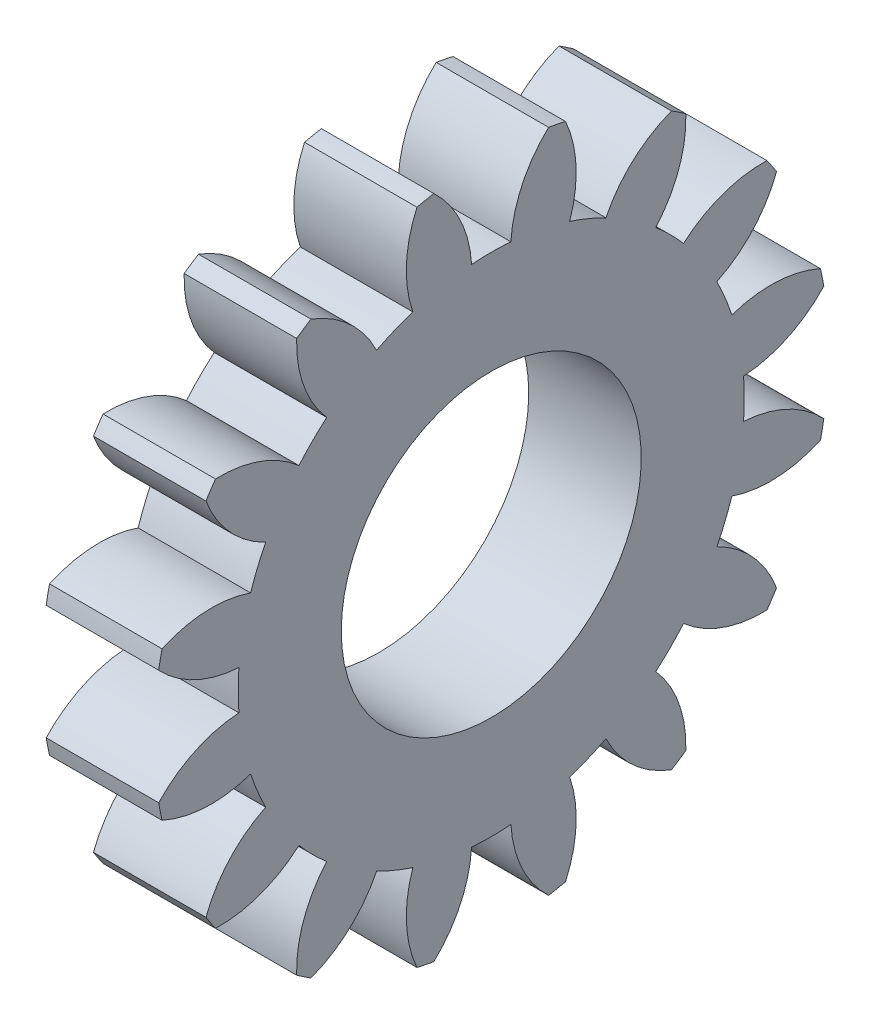
SolidWorks part; units mm, degrees
ref_plane "Plane1" through (0, 0, 0) normal (0, 0, 1) x (1, 0, 0)
ref_plane "Plane2" through (0, 0, 0) normal (0, 1, 0) x (1, 0, 0)
ref_plane "Plane3" through (0, 0, 0) normal (1, 0, 0) x (0, 0, -1)
sketch "HoldingSke" plane through (0, 0, 0) normal (0, 1, 0) x (1, 0, 0)
  line L0 (0, 0) -> (0.9613, -0.2756)
  line L1 (-15, 0) -> (100, 0) construction
  line L2 (0, 0) -> (-2.1039, 2.3779)
  line L3 (0, 0) -> (-11.863, 4.5341)
  line L4 (0, 0) -> (8.3015, 2.3804)
  line L5 (0, 0) -> (-46.8476, -17.4728)
  line L6 (0, 0) -> (-2.4869, -1.6779)
  line L7 (-2.1039, 2.3779) -> (8.6586, 51.2059)
  line L8 (-76.2, 54.61) -> (-74.8, 54.61)
  line L9 (-71.009, 38.7566) -> (-53.1078, 45.2721)
  line L10 (-76.2, 71.12) -> (104.1128, 71.12)
  line L11 (0, 0) -> (-3, 0)
  line L12 (-76.2, 101.6) -> (-76.162, 101.6)
  line L13 (24.9733, 27.94) -> (52.9518, 28.4284)
  line L14 (24.9733, 27.94) -> (24.9743, 27.94)
  line L15 (24.9733, 27.94) -> (100.4006, 29.5858)
  line L16 (-63.627, -1) -> (-12.827, -1)
  circle A0 centre (0, 0) radius 4
  circle A1 centre (0, 0) radius 6.749
  circle A2 centre (0, 0) radius 37.5
  circle A3 centre (0, 0) radius 4
  dimension "MHD" = 13.498
  dimension "Hub_dia" = 75
  dimension "Bore" = 8
  dimension "MBD" = 8
  dimension "Num_teeth" = 16
  dimension "Pitch_radius" = 180.3128
  dimension "Pitch" = 1
  dimension "Width" = 3
  dimension "Overall_len" = 50
  dimension "Show_teeth" = 16
  dimension "Thickness" = 3
  dimension "OAL" = 50.0001
  dimension "T_dim" = 1.4
  dimension "Ap" = 20
  dimension "H" = 19.05
  dimension "Backlash" = 0.038
  dimension "Addendum_fac" = 1
  dimension "Dedendum_fac" = 1.25
  dimension "Clearance_fac" = 0.25
  dimension "Dedendum_add" = 0.001
  dimension "Module" = 1
sketch "BasProSke" plane through (0, 0, 0) normal (0, 1, 0) x (1, 0, 0)
  line L0 (-10, 0) -> (60, 0) construction
  line L1 (0, 0) -> (0, 9)
  line L2 (0, 0) -> (3, 0)
  line L3 (3, 0) -> (3, 9)
  line L4 (3, 9) -> (0, 9)
  dimension "Diameter" = 18
  dimension "Thickness" = 3
revolve "Base-Revolve" add sketch "BasProSke" angle 360 about L0
sketch "TooCutSke" plane through (0, 0, 0) normal (1, 0, 0) x (0, 0, -1)
  line L1 (0, 0) -> (0, 107) construction
  line L2 (0, 0) -> (-0.8506, 7.9547) construction
  line L3 (0, 0) -> (-3.1089, 15.6293) construction
  line L4 (-0.8506, 7.9547) -> (-1.5544, 7.8146) construction
  arc A0 (0.5238, 6.7286) -> (-0.5238, 6.7286) centre (0, 0) ccw
  arc A1 (1.5534, 8.8907) -> (-1.5534, 8.8907) centre (0, 0) ccw
  circle A2 centre (0, 0) radius 8 construction
  circle A3 centre (0, 0) radius 7.5175 construction
  arc A4 (-0.5238, 6.7286) -> (-1.5534, 8.8907) centre (-3.7179, 6.5338) ccw
  arc A5 (1.5534, 8.8907) -> (0.5238, 6.7286) centre (3.7179, 6.5338) ccw
  dimension "Root_dia" = 13.498
  dimension "Overcut_dia" = 18.0508
  dimension "Pitch_dia" = 16
  dimension "Base_dia" = 15.0351
  dimension "Flank_rad" = 3.2
  dimension "Half_ang" = 11.25
  dimension "Half_CT" = 0.7176
extrude "ToothCut" cut sketch "TooCutSke" along normal through all
fillet "Breaks" [suppressed] radius 0.02
fillet "RootFillets" [suppressed] radius 0.251
pattern_circular "TeethCuts" count 16 every 22.5 about axis through (-10, 0, 0) along (1, 0, 0) of "ToothCut", "RootFillets", "Breaks"
sketch "HubNeaOneSke" plane through (0, 0, 0) normal (-1, 0, 0) x (0, 0, 1)
  circle A0 centre (0, 0) radius 6.749
  dimension "Diameter" = 13.498
extrude "HubNearOne" [suppressed] add sketch "HubNeaOneSke" along normal blind 47.0001
sketch "HubNeaBotSke" plane through (0, 0, 0) normal (-1, 0, 0) x (0, 0, 1)
  circle A0 centre (0, 0) radius 6.749
  dimension "Diameter" = 13.498
extrude "HubNearBoth" [suppressed] add sketch "HubNeaBotSke" along normal blind 23.5
ref_plane "FarPln" through (3, 0, 0) normal (1, 0, 0) x (0, 0, -1)
sketch "HubFarSke" plane through (3, 0, 0) normal (1, 0, 0) x (0, 0, -1)
  circle A0 centre (0, 0) radius 6.749
  dimension "Diameter" = 13.498
extrude "HubFar" [suppressed] add sketch "HubFarSke" along normal blind 23.5
sketch "BorSke" plane through (0, 0, 0) normal (1, 0, 0) x (0, 0, -1)
  circle A0 centre (0, 0) radius 4
  dimension "Diameter" = 8
extrude "Bore" cut sketch "BorSke" along normal mid plane 100.0001
sketch "KeySke" plane through (0, 0, 0) normal (1, 0, 0) x (0, 0, -1)
  line L0 (-1.5, 0) -> (-1.5, 5.4)
  line L1 (-1.5, 5.4) -> (1.5, 5.4)
  line L2 (1.5, 5.4) -> (1.5, 0)
  line L3 (0, 0) -> (0, 34) construction
  line L4 (-1.5, 0) -> (1.5, 0)
  dimension "Offset" = 5.4
  dimension "Width" = 3
extrude "Keyway" [suppressed] cut sketch "KeySke" along normal mid plane 100.0001
pattern_circular "Keyway2" [suppressed] count 2 every 90 about axis through (-10, 0, 0) along (1, 0, 0)
equation "' \"Module@HoldingSke\" = 6.35"
equation "' \"Num_teeth@HoldingSke\" = 12"
equation "' \"Ap@HoldingSke\" =  20"
equation "' \"Width@HoldingSke\" = 0.5 * 25.4"
equation "' \"Hub_dia@HoldingSke\"= 1 * 25.4"
equation "' \"Overall_len@HoldingSke\" = 1.0 * 25.4"
equation "' \"Bore@HoldingSke\" = 0.75 * 25.4"
equation "' \"T_dim@HoldingSke\" = 0.1 * 25.4"
equation "' \"Width@KeySke\" = 0.25 * 25.4"
equation "' \"Show_teeth@HoldingSke\" = 13"
equation "' \"Backlash@HoldingSke\" = 0.009 * 25.4"
equation "' \"Addendum_fac@HoldingSke\" = 1.0"
equation "' \"Dedendum_fac@HoldingSke\" = 1.25"
equation "' \"Dedendum_add@HoldingSke\" = 0.00005 * 25.4"
equation "' \"Clearance_fac@HoldingSke\" = 0.25"
equation "\"Pitch@HoldingSke\" = 1 / \"Module@HoldingSke\""
equation "\"Overcut_dia@TooCutSke\" = (\"Num_teeth@HoldingSke\" + 2 * \"Addendum_fac@HoldingSke\") / \"Pitch@HoldingSke\" + 0.002 * 25.4"
equation "\"Pitch_dia@TooCutSke\" = \"Num_teeth@HoldingSke\" / \"Pitch@HoldingSke\""
equation "\"Base_dia@TooCutSke\" = \"Num_teeth@HoldingSke\" / \"Pitch@HoldingSke\" * cos((\"Ap@HoldingSke\"  * 3.14159265 / 180))"
equation "\"Root_dia@TooCutSke\" = (\"Num_teeth@HoldingSke\" + 2) / \"Pitch@HoldingSke\" - 2 * (\"Addendum_fac@HoldingSke\" + \"Dedendum_fac@HoldingSke\") / \"Pitch@HoldingSke\" - \"Dedendum_add@HoldingSke\" * 2"
equation "\"Half_ang@TooCutSke\" = 180 / \"Num_teeth@HoldingSke\""
equation "\"Half_CT@TooCutSke\" = \"Num_teeth@HoldingSke\" / \"Pitch@HoldingSke\" * sin((3.14159265 / 2 / \"Num_teeth@HoldingSke\")) / 2 - 7 * \"Backlash@HoldingSke\" / 4"
equation "\"Flank_rad@TooCutSke\" = \"Num_teeth@HoldingSke\" / \"Pitch@HoldingSke\" / 5"
equation "\"Radius@RootFillets\" = \"Clearance_fac@HoldingSke\" / \"Pitch@HoldingSke\" + \"Dedendum_add@HoldingSke\""
equation "\"Break_rad@Breaks\" = 0.02 / \"Pitch@HoldingSke\""
equation "\"Thickness@HoldingSke\" = \"Width@HoldingSke\""
equation "\"OAL@HoldingSke\" = \"Thickness@HoldingSke\""
equation "\"MHD@HoldingSke\" = (\"Num_teeth@HoldingSke\" + 2) / \"Pitch@HoldingSke\" - 2 * (\"Addendum_fac@HoldingSke\" + \"Dedendum_fac@HoldingSke\")  / \"Pitch@HoldingSke\" - \"Dedendum_add@HoldingSke\" * 2"
equation "\"MBD@HoldingSke\" = (\"Num_teeth@HoldingSke\" + 2) / \"Pitch@HoldingSke\" - 2 * (\"Addendum_fac@HoldingSke\" + \"Dedendum_fac@HoldingSke\")  / \"Pitch@HoldingSke\" - \"Dedendum_add@HoldingSke\" * 2 - 0.002 * 25.4"
equation "\"MHD@HoldingSke\" = ((sgn( \"MHD@HoldingSke\" - \"Hub_dia@HoldingSke\" )-1)*( \"MHD@HoldingSke\" - \"Hub_dia@HoldingSke\" ))/-2+ \"Hub_dia@HoldingSke\""
equation "\"MBD@HoldingSke\" = ((sgn( \"MBD@HoldingSke\" - \"Bore@HoldingSke\" )-1)*( \"MBD@HoldingSke\" - \"Bore@HoldingSke\" ))/-2+ \"Bore@HoldingSke\""
equation "\"OAL@HoldingSke\" = ((sgn( \"OAL@HoldingSke\" - \"Overall_len@HoldingSke\" )+1)*( \"OAL@HoldingSke\" - \"Overall_len@HoldingSke\" ))/2 + \"Overall_len@HoldingSke\" + 0.000002 * 25.4"
equation "\"Num_teeth@TeethCuts\" = int( \"Show_teeth@HoldingSke\" ) + 1"
equation "\"Num_teeth@TeethCuts\" = ((sgn( \"Num_teeth@TeethCuts\" - \"Num_teeth@HoldingSke\" )-1)*( \"Num_teeth@TeethCuts\" - \"Num_teeth@HoldingSke\" ))/-2+ \"Num_teeth@HoldingSke\""
equation "\"Num_teeth@TeethCuts\" = ((sgn( \"Num_teeth@TeethCuts\" - 2.0)+1)*( \"Num_teeth@TeethCuts\" - 2.0))/2 +2.0"
equation "\"Angle@TeethCuts\" = 360.0 / \"Num_teeth@HoldingSke\""
equation "\"Diameter@BasProSke\" = (\"Num_teeth@HoldingSke\" + 2 * \"Addendum_fac@HoldingSke\") / \"Pitch@HoldingSke\""
equation "\"Thickness@BasProSke\"  = \"Thickness@HoldingSke\""
equation "' \"Fillet_rad@BasProSke\" =  \"Thickness@HoldingSke\" * 0.05"
equation "\"MHD@HoldingSke\" = ((sgn( \"MHD@HoldingSke\" - \"Root_dia@TooCutSke\" )-1)*( \"MHD@HoldingSke\" - \"Root_dia@TooCutSke\" ))/-2+ \"Root_dia@TooCutSke\""
equation "\"Diameter@HubNeaOneSke\" = \"MHD@HoldingSke\""
equation "\"Length@HubNearOne\" = \"OAL@HoldingSke\" - \"Thickness@BasProSke\""
equation "\"Diameter@HubNeaBotSke\" = \"MHD@HoldingSke\""
equation "\"Length@HubNearBoth\" = ( \"OAL@HoldingSke\" - \"Thickness@BasProSke\" ) / 2.0"
equation "\"Thickness@FarPln\" = \"Thickness@BasProSke\""
equation "\"Diameter@HubFarSke\" = \"MHD@HoldingSke\""
equation "\"Length@HubFar\" = ( \"OAL@HoldingSke\" - \"Thickness@BasProSke\" ) / 2.0"
equation "\"Diameter@BorSke\" = \"MBD@HoldingSke\""
equation "\"D1@Bore\" = \"OAL@HoldingSke\" * 2.0"
equation "\"D1@Keyway\" = \"OAL@HoldingSke\" * 2.0"
equation "\"Offset@KeySke\" = \"T_dim@HoldingSke\" + \"MBD@HoldingSke\" / 2.0"
